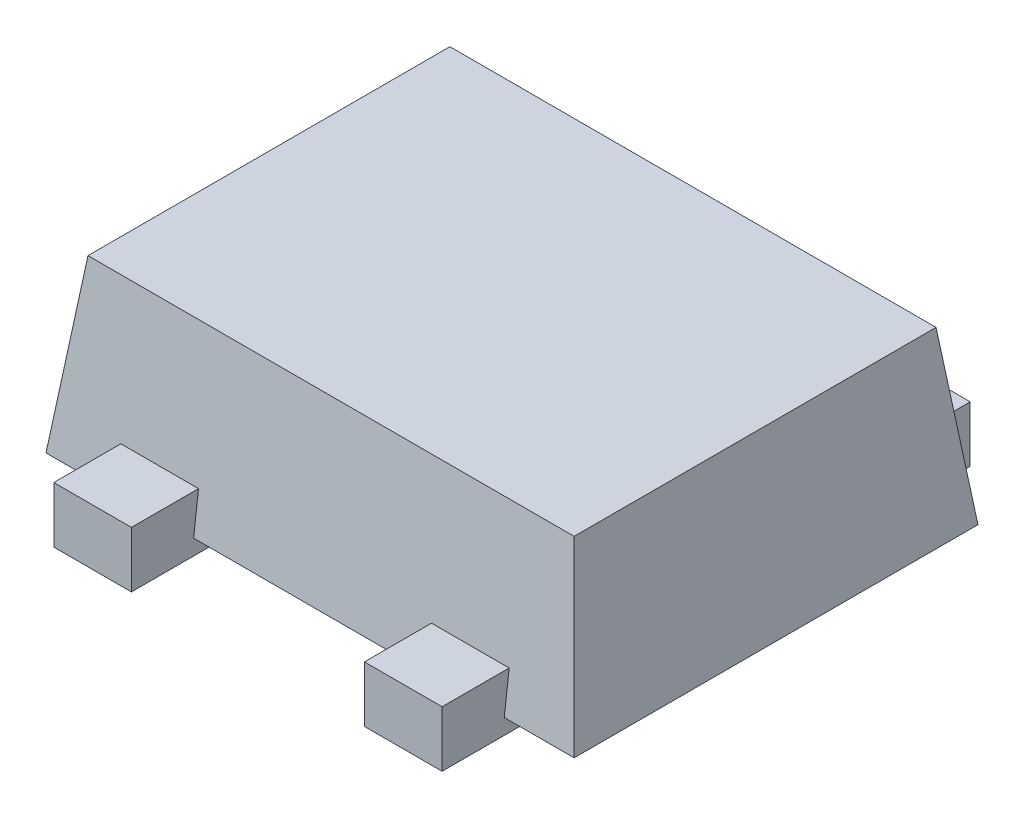
SolidWorks part; units mm, degrees
ref_plane "Alzado" through (0, 0, 0) normal (0, 0, 1) x (1, 0, 0)
ref_plane "Planta" through (0, 0, 0) normal (0, 1, 0) x (1, 0, 0)
ref_plane "Vista lateral" through (0, 0, 0) normal (1, 0, 0) x (0, 0, -1)
sketch "Croquis1" plane through (0, 0, 0) normal (0, 1, 0) x (1, 0, 0)
  line L1 (-0.85, -0.65) -> (0.85, -0.65)
  line L2 (-0.85, -0.65) -> (-0.85, 0.65)
  line L3 (-0.85, 0.65) -> (0.85, 0.65)
  line L4 (0.85, -0.65) -> (0.85, 0.65)
  line L5 (-0.85, -0.65) -> (0.85, 0.65) construction
  line L6 (-0.85, 0.65) -> (0.85, -0.65) construction
  point P0 (0, 0)
  dimension "D1" = 1.7
  dimension "D2" = 1.3
extrude "Saliente-Extruir1" add sketch "Croquis1" along normal blind 0.55 draft 7
sketch "Croquis2" plane through (0, 0, 0) normal (1, 0, 0) x (0, 0, -1)
  line L0 (0, 0.04) -> (0.85, 0.04) construction
  line L1 (0.65, -0.05) -> (0.65, 0.13) construction
  dimension "D1" = 0.85
  dimension "D2" = 0.18
ref_plane "Plano1" through (0, 0.04, -0.85) normal (0, 0, -1) x (-1, 0, 0)
sketch "Croquis3" plane through (0, 0.04, -0.85) normal (0, 0, -1) x (-1, 0, 0)
  line L1 (-0.125, -0.09) -> (0.125, -0.09)
  line L2 (-0.125, -0.09) -> (-0.125, 0.09)
  line L3 (-0.125, 0.09) -> (0.125, 0.09)
  line L4 (0.125, -0.09) -> (0.125, 0.09)
  line L5 (-0.125, -0.09) -> (0.125, 0.09) construction
  line L6 (-0.125, 0.09) -> (0.125, -0.09) construction
  point P0 (0, 0)
  dimension "D1" = 0.25
  dimension "D2" = 0.18
extrude "Saliente-Extruir2" add sketch "Croquis3" against normal blind 0.4 separate body
pattern_linear "MatrizL1" count 2 spacing 0.5 along (1, 0, 0) of "Saliente-Extruir2"
pattern_linear "MatrizL2" count 2 spacing 0.5 along (-1, 0, 0) of "Saliente-Extruir2"
ref_plane "Plano2" through (0.5, 0, 0) normal (1, 0, 0) x (0, 0, -1)
sketch "Croquis5" plane through (0.5, 0, 0) normal (1, 0, 0) x (0, 0, -1)
  line L0 (0, 0.04) -> (-0.85, 0.04) construction
  dimension "D1" = 0.85
ref_plane "Plano3" through (0.5, 0.04, 0.85) normal (0, 0, 1) x (1, 0, 0)
sketch "Croquis6" plane through (0.5, 0.04, 0.85) normal (0, 0, 1) x (1, 0, 0)
  line L1 (-0.125, 0.09) -> (0.125, 0.09)
  line L2 (-0.125, 0.09) -> (-0.125, -0.09)
  line L3 (-0.125, -0.09) -> (0.125, -0.09)
  line L4 (0.125, 0.09) -> (0.125, -0.09)
  line L5 (-0.125, 0.09) -> (0.125, -0.09) construction
  line L6 (-0.125, -0.09) -> (0.125, 0.09) construction
  point P0 (0, 0)
  dimension "D1" = 0.18
  dimension "D2" = 0.25
extrude "Saliente-Extruir3" add sketch "Croquis6" against normal blind 0.4 separate body
pattern_linear "MatrizL3" count 2 spacing 1 along (-1, 0, 0) of "Saliente-Extruir3"
